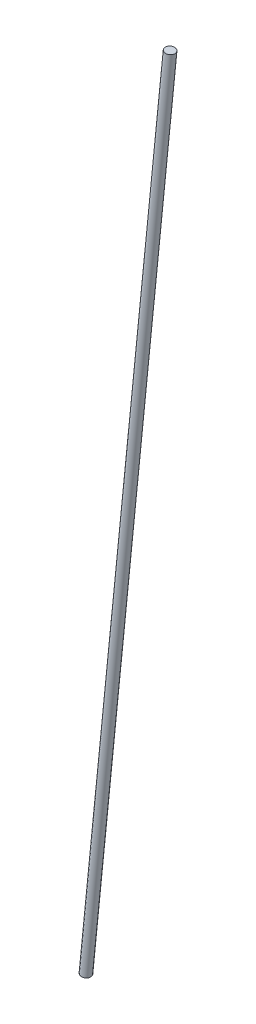
SolidWorks part; units mm, degrees
ref_plane "前基準面" through (0, 0, 0) normal (0, 0, 1) x (1, 0, 0)
ref_plane "上基準面" through (0, 0, 0) normal (0, 1, 0) x (1, 0, 0)
ref_plane "右基準面" through (0, 0, 0) normal (1, 0, 0) x (0, 0, -1)
sketch "草圖1" plane through (0, 0, 0) normal (0, 0, 1) x (1, 0, 0)
  line L6 (125, 250) -> (100, 0) construction
  line L7 (0, 0) -> (25.9901, 259.901)
  line L8 (0, 0) -> (1.4926, -0.1493)
  line L9 (25.9901, 259.901) -> (27.4827, 259.7517)
  line L10 (1.4926, -0.1493) -> (27.4827, 259.7517)
  dimension "D1" = 250
  dimension "D2" = 100
  dimension "D3" = 125
  dimension "D4" = 1.5
revolve "旋轉1" add sketch "草圖1" angle 360 about L7
